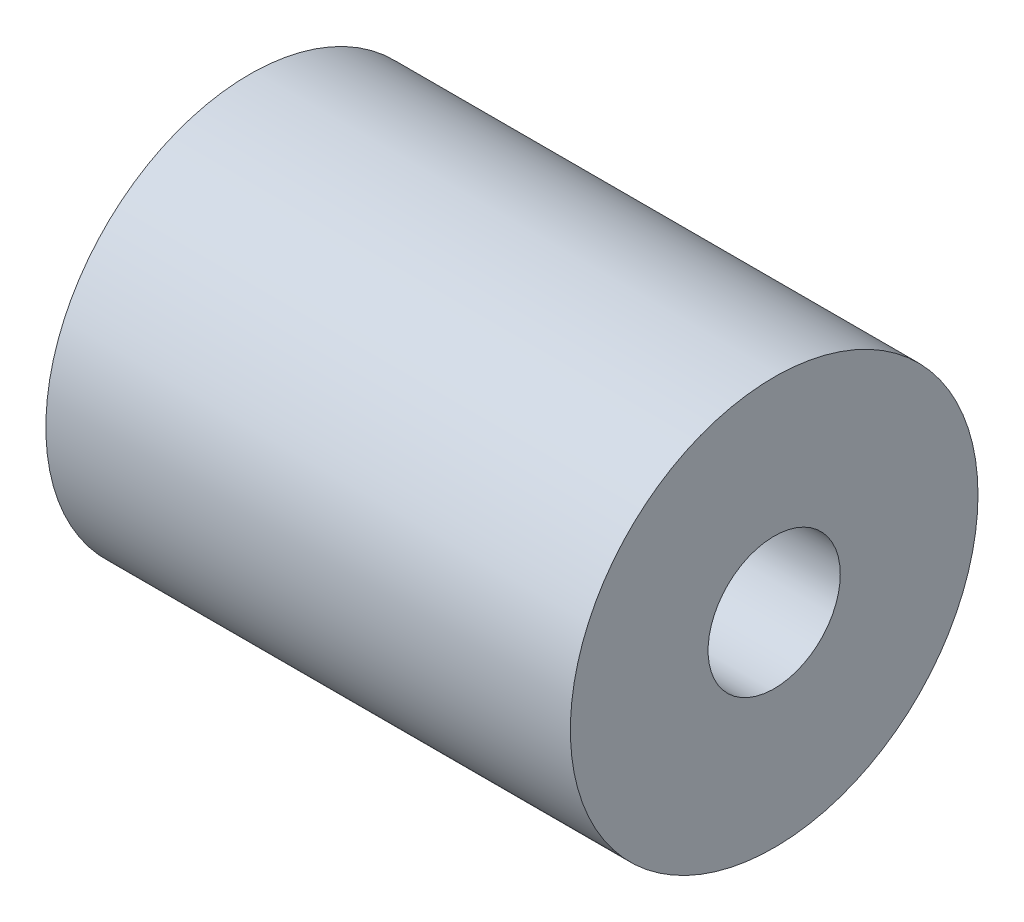
SolidWorks part; units mm, degrees
ref_plane "Front Plane" through (0, 0, 0) normal (0, 0, 1) x (1, 0, 0)
ref_plane "Top Plane" through (0, 0, 0) normal (0, 1, 0) x (1, 0, 0)
ref_plane "Right Plane" through (0, 0, 0) normal (1, 0, 0) x (0, 0, -1)
sketch "Sketch1" plane through (0, 0, 0) normal (1, 0, 0) x (0, 0, -1)
  line L0 (0, 9.465) -> (0, 0) construction
  line L1 (0, 0) -> (0, -9.465) construction
  circle A0 centre (0, 9.465) radius 3.15
  circle A1 centre (0, -9.465) radius 3.15 construction
  circle A2 centre (0, 9.465) radius 9.715
  circle A3 centre (0, -9.465) radius 9.715 construction
  dimension "D2" = 6.3
  dimension "D3" = 19.43
  dimension "D1" = 18.93
extrude "Boss-Extrude1" add sketch "Sketch1" along normal blind 25
